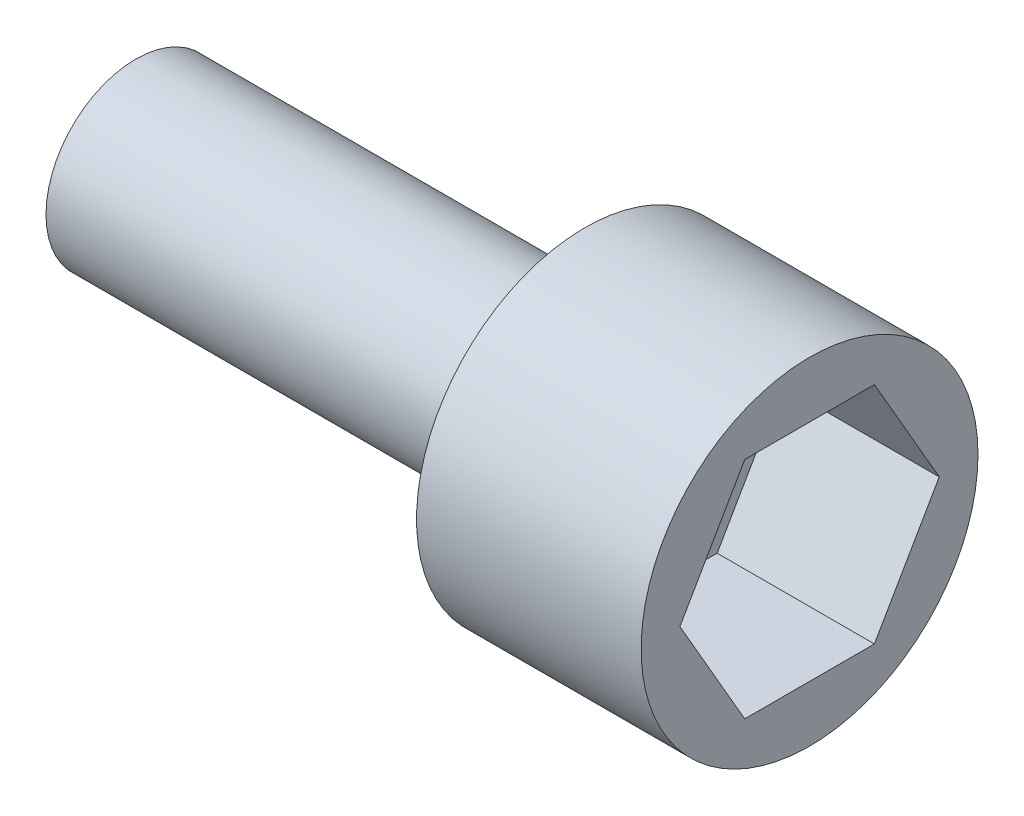
SolidWorks part; units mm, degrees
ref_plane "Front Plane" through (0, 0, 0) normal (0, 0, 1) x (1, 0, 0)
ref_plane "Top Plane" through (0, 0, 0) normal (0, 1, 0) x (1, 0, 0)
ref_plane "Right Plane" through (0, 0, 0) normal (1, 0, 0) x (0, 0, -1)
sketch "Sketch1" plane through (0, 0, 0) normal (0, 0, 1) x (1, 0, 0)
  line L0 (0, 0) -> (0, 4)
  line L1 (0, 4) -> (20, 4)
  line L2 (20, 4) -> (20, 7.5)
  line L3 (20, 7.5) -> (30, 7.5)
  line L4 (30, 7.5) -> (30, 0)
  line L5 (30, 0) -> (0, 0)
  dimension "D1" = 30
  dimension "D2" = 4
  dimension "D3" = 20
  dimension "D4" = 7.5
revolve "Revolve1" add sketch "Sketch1" angle 360 about L5
sketch "Sketch2" plane through (30, 0, 0) normal (1, 0, 0) x (0, 0, -1)
  line L1 (5.7735, 0) -> (2.8868, 5)
  line L2 (2.8868, 5) -> (-2.8868, 5)
  line L3 (-2.8868, 5) -> (-5.7735, 0)
  line L4 (-5.7735, 0) -> (-2.8868, -5)
  line L5 (-2.8868, -5) -> (2.8868, -5)
  line L6 (2.8868, -5) -> (5.7735, 0)
  circle A0 centre (0, 0) radius 5 construction
  point P1 (0, 0)
  dimension "D1" = 10
extrude "Cut-Extrude1" cut sketch "Sketch2" against normal blind 7
